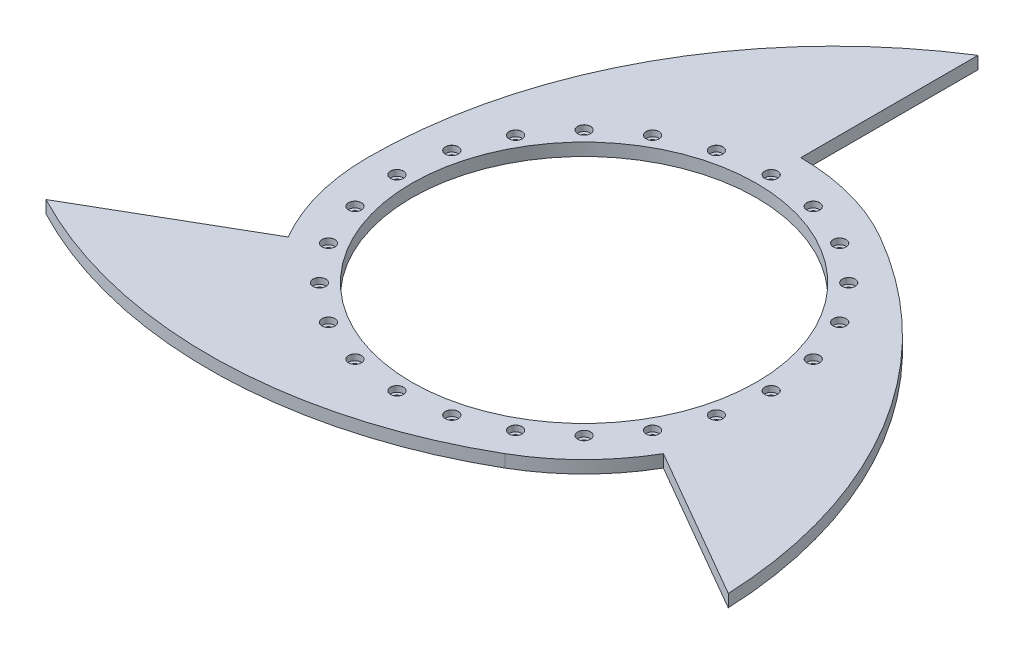
SolidWorks part; units mm, degrees
material "Delrin 2700 NC010, Low Viscosity Acetal Copolymer (SS)"
ref_plane "Front Plane" through (0, 0, 0) normal (0, 0, 1) x (1, 0, 0)
ref_plane "Top Plane" through (0, 0, 0) normal (0, 1, 0) x (1, 0, 0)
ref_plane "Right Plane" through (0, 0, 0) normal (1, 0, 0) x (0, 0, -1)
sketch "Sketch1" plane through (0, 0, 0) normal (0, 1, 0) x (1, 0, 0)
  line L0 (0, 0) -> (0, 200) construction
  line L1 (0, 200) -> (0, 110)
  line L2 (0, 0) -> (-110, 0) construction
  line L3 (173.2051, -100) -> (95.2628, -55)
  line L4 (-173.2051, -100) -> (-95.2628, -55)
  circle A0 centre (0, 0) radius 87.5
  arc A1 (55, -95.2628) -> (95.2628, -55) centre (0, 0) ccw
  arc A2 (-110, 0) -> (0, 200) centre (126.8182, 0) cw
  arc A3 (55, 95.2628) -> (173.2051, -100) centre (-63.4091, -109.8278) cw
  arc A4 (55, -95.2628) -> (-173.2051, -100) centre (-63.4091, 109.8278) cw
  arc A5 (55, 95.2628) -> (0, 110) centre (0, 0) ccw
  arc A6 (-110, 0) -> (-95.2628, -55) centre (0, 0) ccw
  point P18 (0, 0)
  dimension "D1" = 175
  dimension "D2" = 220
  dimension "D3" = 90
  dimension "D4" = 200
  dimension "D5" = 3
extrude "Boss-Extrude1" add sketch "Sketch1" along normal blind 6.35
hole_wizard "CBORE for M3 SHCS1" positions "Sketch2" profile "Sketch3" counterbore size "M3" standard "ANSI Metric" end condition through all
sketch "Sketch2" plane through (0, 6.35, 0) normal (0, 1, 0) x (1, 0, 0)
  line L0 (0, 0) -> (95, 0) construction
  point P0 (95, 0)
  point P15 (91.763, -24.5878)
  point P16 (82.2724, -47.5)
  point P17 (67.1751, -67.1751)
  point P18 (47.5, -82.2724)
  point P19 (24.5878, -91.763)
  point P20 (0, -95)
  point P21 (-24.5878, -91.763)
  point P22 (-47.5, -82.2724)
  point P23 (-67.1751, -67.1751)
  point P24 (-82.2724, -47.5)
  point P25 (-91.763, -24.5878)
  point P26 (-95, 0)
  point P27 (-91.763, 24.5878)
  point P28 (-82.2724, 47.5)
  point P29 (-67.1751, 67.1751)
  point P30 (-47.5, 82.2724)
  point P31 (-24.5878, 91.763)
  point P32 (0, 95)
  point P33 (24.5878, 91.763)
  point P34 (47.5, 82.2724)
  point P35 (67.1751, 67.1751)
  point P36 (82.2724, 47.5)
  point P37 (91.763, 24.5878)
  point P38 (0, 0)
  dimension "D1" = 95
  dimension "D2" = 24
sketch "Sketch3" plane through (95, 6.35, 0) normal (1, 0, 0) x (0, 0, 1)
  line L0 (0, 0) -> (0, 6.35)
  line L1 (0, 6.35) -> (1.6, 6.35)
  line L3 (1.6, 6.35) -> (1.6, 3)
  line L4 (3.25, 3) -> (1.6, 3)
  line L5 (3.25, 3) -> (3.25, 0.025)
  line L6 (3.25, 0.025) -> (3.275, 0)
  line L7 (3.275, 0) -> (0, 0)
  line L8 (-3.25, 0.025) -> (-3.275, 0) construction
  line L11 (0, -6.35) -> (0, 107.95) construction
  dimension "Thru Hole Dia." = 3.2
  dimension "Thru Hole Depth" = 6.35
  dimension "C'Bore Dia." = 6.5
  dimension "C'Bore Depth" = 3
  dimension "Near C'Sink Dia." = 6.55
  dimension "Near C'Sink Angle" = 90
